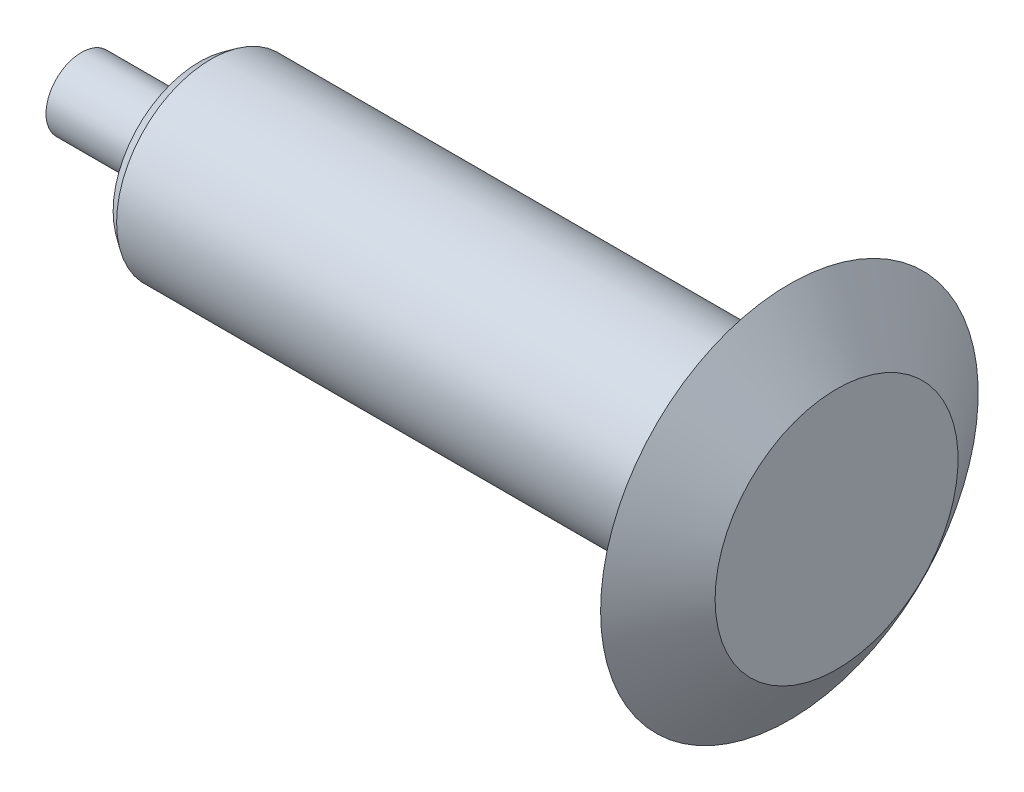
SolidWorks part; units mm, degrees
ref_plane "Alzado" through (0, 0, 0) normal (0, 0, 1) x (1, 0, 0)
ref_plane "Planta" through (0, 0, 0) normal (0, 1, 0) x (1, 0, 0)
ref_plane "Vista lateral" through (0, 0, 0) normal (1, 0, 0) x (0, 0, -1)
sketch "Croquis1" plane through (0, 0, 0) normal (0, 0, 1) x (1, 0, 0)
  line L0 (0, 0) -> (0, 25.7421)
  line L1 (0, 25.7421) -> (-10, 40)
  line L2 (-10, 40) -> (-10, 25.7421)
  line L3 (-10, 25.7421) -> (-18.1871, 20)
  line L4 (-18.1871, 20) -> (-132.5439, 20)
  line L5 (-132.5439, 20) -> (-135, 18.2774)
  line L6 (-135, 18.2774) -> (-135, 7.5)
  line L7 (-135, 7.5) -> (-160, 7.5)
  line L8 (-160, 7.5) -> (-160, 0)
  line L9 (-160, 0) -> (0, 0)
  point P10 (0, 0)
  point P12 (-10, 30)
  point P13 (-10, 30)
  point P14 (0, 0)
  dimension "D1" = 40
  dimension "D2" = 150
  dimension "D3" = 25
  dimension "D4" = 160
  dimension "D5" = 7.5
  dimension "D6" = 10
  dimension "D7" = 20
  dimension "D8" = 3
revolve "Revolución1" add sketch "Croquis1" angle 360 about L9
